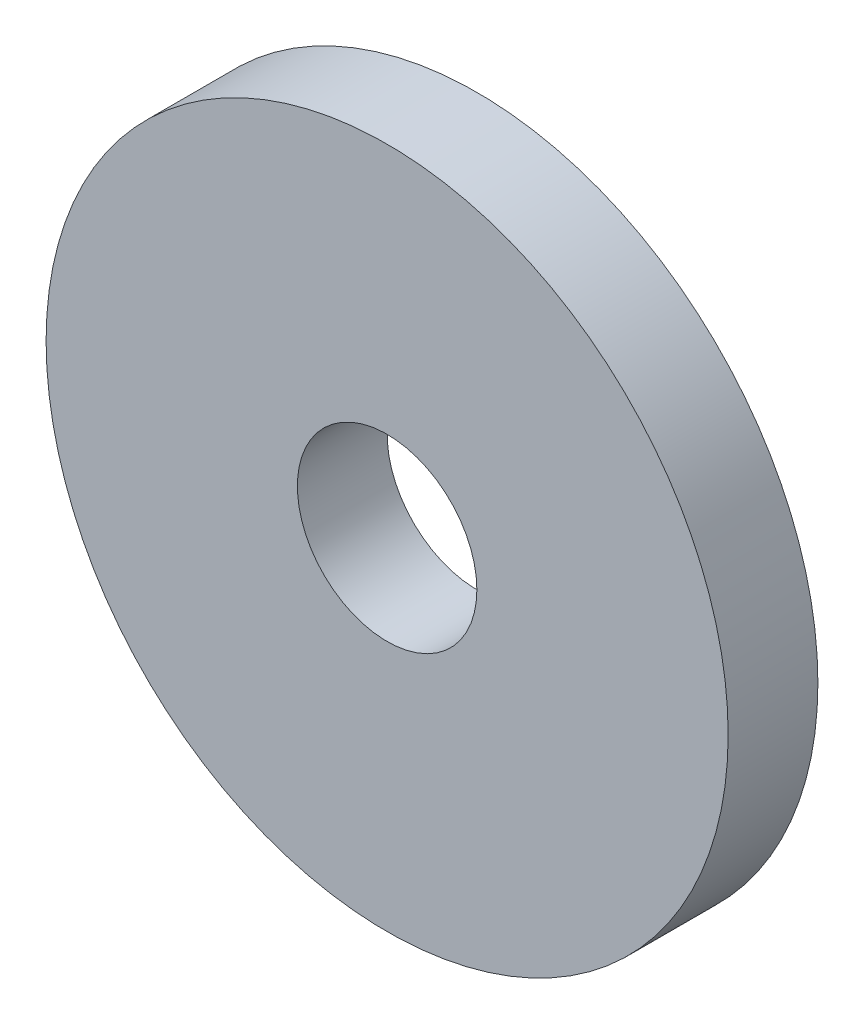
SolidWorks part; units mm, degrees
ref_plane "Front Plane" through (0, 0, 0) normal (0, 0, 1) x (1, 0, 0)
ref_plane "Top Plane" through (0, 0, 0) normal (0, 1, 0) x (1, 0, 0)
ref_plane "Right Plane" through (0, 0, 0) normal (1, 0, 0) x (0, 0, -1)
sketch "Sketch1" plane through (0, 0, 0) normal (0, 0, 1) x (1, 0, 0)
  circle A0 centre (0, 0) radius 9.5
  circle A1 centre (0, 0) radius 2.5
  dimension "D1" = 5
  dimension "D2" = 19
extrude "Boss-Extrude1" add sketch "Sketch1" along normal blind 2.5
